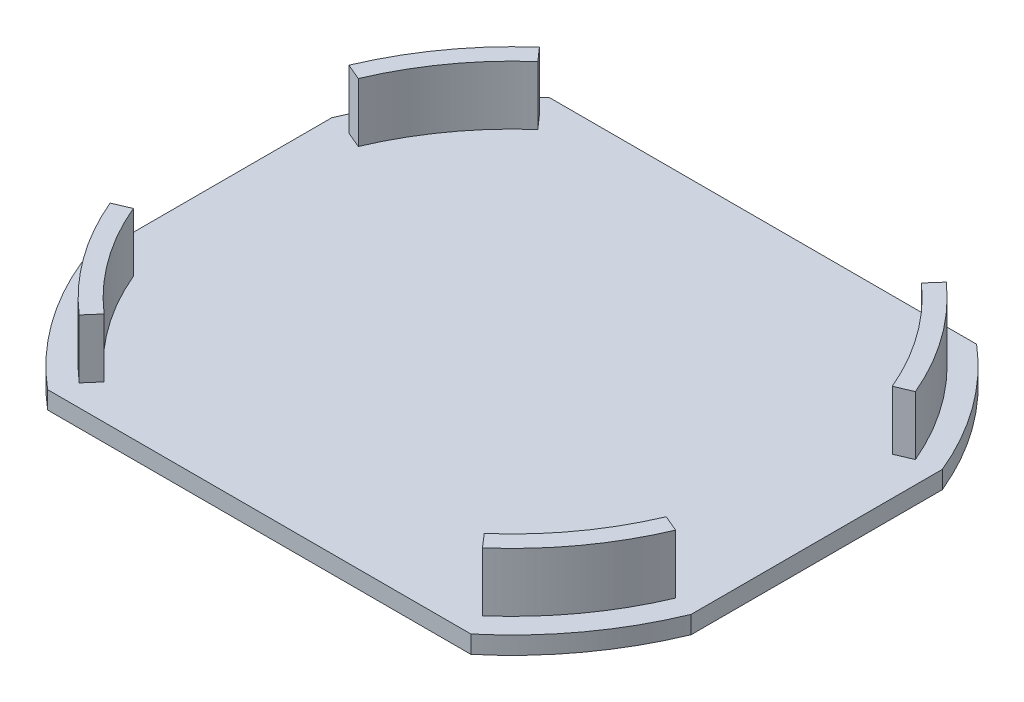
SolidWorks part; units mm, degrees
ref_plane "Front Plane" through (0, 0, 0) normal (0, 0, 1) x (1, 0, 0)
ref_plane "Top Plane" through (0, 0, 0) normal (0, 1, 0) x (1, 0, 0)
ref_plane "Right Plane" through (0, 0, 0) normal (1, 0, 0) x (0, 0, -1)
sketch "Sketch1" plane through (0, 0, 0) normal (0, 1, 0) x (1, 0, 0)
  line L8 (-6.9007, 0) -> (7.9319, 0) construction
  line L9 (0, 7.9961) -> (0, -5.1117) construction
  line L10 (-11, -12) -> (11, -12)
  line L11 (17, 8.5) -> (23, 8.5)
  line L12 (17, 8.5) -> (17, -8.5)
  line L13 (17, -8.5) -> (23, -8.5)
  line L14 (23, 8.5) -> (23, -8.5)
  line L15 (17, 8.5) -> (23, -8.5) construction
  line L16 (17, -8.5) -> (23, 8.5) construction
  line L17 (-11, 19) -> (11, 19)
  line L18 (-11, 19) -> (-11, 12)
  line L19 (-11, 12) -> (11, 12)
  line L20 (11, 19) -> (11, 12)
  line L21 (-11, 19) -> (11, 12) construction
  line L22 (-11, 12) -> (11, 19) construction
  line L23 (11, -19) -> (11, -12)
  line L24 (-11, -19) -> (11, -19)
  line L25 (-11, -19) -> (-11, -12)
  line L34 (17.4593, -20.0682) -> (-17.4593, -20.0682) construction
  line L35 (-24.5102, 10.335) -> (-24.5102, -10.335) construction
  line L36 (-25.9102, 10.6143) -> (-25.9102, -10.6143)
  line L37 (17.9755, -21.4682) -> (-17.9755, -21.4682)
  line L38 (25.8898, 10.6638) -> (25.8898, -10.6638)
  line L39 (-18.1371, 21.3318) -> (18.1371, 21.3318)
  line L41 (-17.6148, 19.9318) -> (17.6148, 19.9318) construction
  line L42 (-17.6148, 19.9318) -> (17.6148, 19.9318) construction
  line L43 (24.4898, 10.3831) -> (24.4898, -10.3831) construction
  line L44 (24.4898, 10.3831) -> (24.4898, -10.3831) construction
  arc A12 (-25.9102, -10.6143) -> (-17.9755, -21.4682) centre (0, 0) ccw
  arc A13 (17.9755, -21.4682) -> (25.8898, -10.6638) centre (0, 0) ccw
  arc A14 (25.8898, 10.6638) -> (18.1371, 21.3318) centre (0, 0) ccw
  arc A15 (-18.1371, 21.3318) -> (-25.9102, 10.6143) centre (0, 0) ccw
  arc A20 (24.4898, 10.3831) -> (17.6148, 19.9318) centre (0, 0) ccw construction
  arc A25 (17.4593, -20.0682) -> (24.4898, -10.3831) centre (0, 0) ccw construction
  arc A33 (-24.5102, -10.335) -> (-17.4593, -20.0682) centre (0, 0) ccw construction
  arc A35 (-17.6148, 19.9318) -> (-24.5102, 10.335) centre (0, 0) ccw construction
  point P0 (-24.5102, 0)
  point P1 (0, -20.0682)
  point P14 (0, 19.9318)
  point P15 (25.8898, 0)
  point P16 (0, -21.4682)
  point P29 (20, 0)
  point P34 (0, 15.5)
  point P43 (0, 0)
  dimension "D17" = 26.6
  dimension "D2" = 1.4
  dimension "D7" = 17
  dimension "D8" = 6
  dimension "D9" = 20
  dimension "D10" = 22
  dimension "D11" = 7
  dimension "D12" = 15.5
extrude "Boss-Extrude1" add sketch "Sketch1" along normal blind 1.5 contours L35 A33 L34 A25 L43 A20 L42 A35 | L36 A12 L37 A13 L38 A14 L39 A15
sketch "Sketch2" plane through (0, 1.5, 0) normal (0, 1, 0) x (1, 0, 0)
  line L0 (17.4593, -20.0123) -> (-17.4593, -20.0123) construction
  line L1 (-24.5102, 10.3908) -> (-24.5102, -10.2791) construction
  line L2 (-17.6148, 19.9877) -> (17.6148, 19.9877) construction
  line L3 (24.4898, 10.4389) -> (24.4898, -10.3272) construction
  line L4 (-17.2837, 19.613) -> (-16.2904, 18.489)
  line L5 (-24.0495, 10.1965) -> (-22.6673, 9.6137)
  line L6 (17.2837, 19.613) -> (16.2904, 18.489)
  line L7 (22.6485, 9.6583) -> (24.0295, 10.2438)
  line L8 (22.6485, -9.5466) -> (24.0295, -10.1321)
  line L9 (16.1466, -18.5034) -> (17.1312, -19.6351)
  line L10 (-24.0495, -10.0848) -> (-22.6673, -9.502)
  line L11 (-16.1466, -18.5034) -> (-17.1312, -19.6351)
  arc A0 (24.4898, 10.4389) -> (17.6148, 19.9877) centre (0, 0.0558) ccw construction
  arc A1 (17.4593, -20.0123) -> (24.4898, -10.3272) centre (0, 0.0558) ccw construction
  arc A2 (-24.5102, -10.2791) -> (-17.4593, -20.0123) centre (0, 0.0558) ccw construction
  arc A3 (-17.6148, 19.9877) -> (-24.5102, 10.3908) centre (0, 0.0558) ccw construction
  arc A4 (-17.2837, 19.613) -> (-24.0495, 10.1965) centre (0, 0.0558) ccw
  arc A5 (24.0295, 10.2438) -> (17.2837, 19.613) centre (0, 0.0558) ccw
  arc A6 (-24.0495, -10.0848) -> (-17.1312, -19.6351) centre (0, 0.0558) ccw
  arc A7 (17.1312, -19.6351) -> (24.0295, -10.1321) centre (0, 0.0558) ccw
  arc A8 (-16.2904, 18.489) -> (-22.6673, 9.6137) centre (0, 0.0558) ccw
  arc A9 (22.6485, 9.6583) -> (16.2904, 18.489) centre (0, 0.0558) ccw
  arc A10 (16.1466, -18.5034) -> (22.6485, -9.5466) centre (0, 0.0558) ccw
  arc A11 (-22.6673, -9.502) -> (-16.1466, -18.5034) centre (0, 0.0558) ccw
  dimension "D1" = 0.5
  dimension "D2" = 1.5
extrude "Boss-Extrude2" add sketch "Sketch2" along normal blind 5
